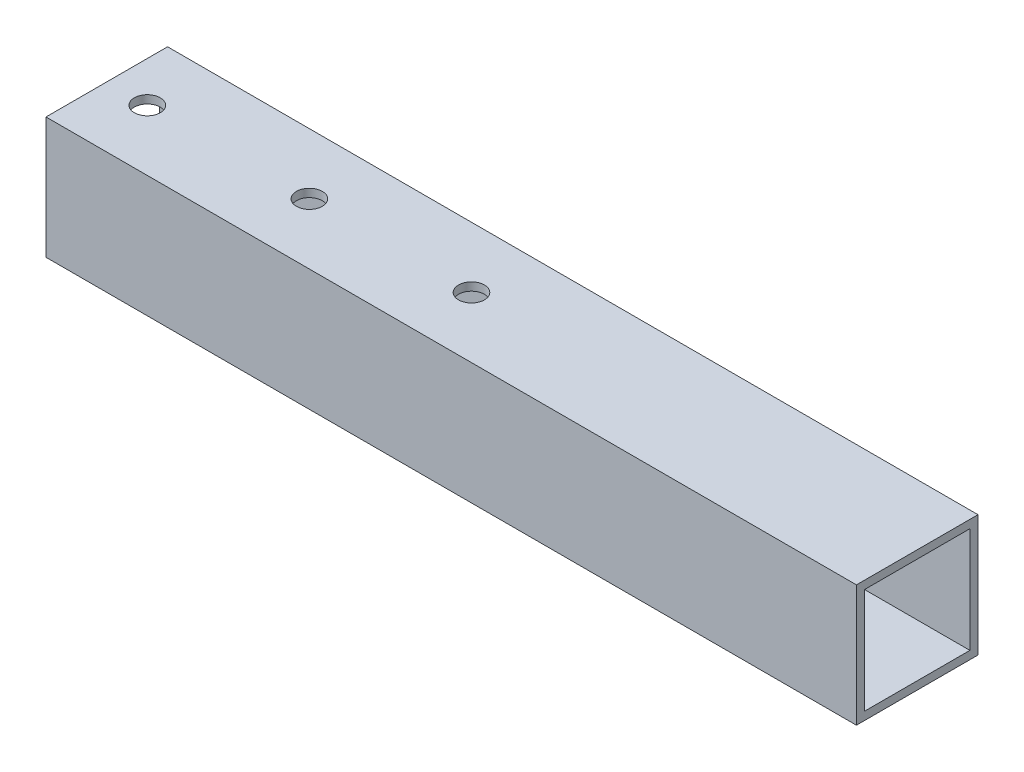
SolidWorks part; units mm, degrees
material "Thornel Mat VMA"
ref_plane "前视基准面" through (0, 0, 0) normal (0, 0, 1) x (1, 0, 0)
ref_plane "上视基准面" through (0, 0, 0) normal (0, 1, 0) x (1, 0, 0)
ref_plane "右视基准面" through (0, 0, 0) normal (1, 0, 0) x (0, 0, -1)
other "Configuration Table"
sketch "草图1" plane through (0, 0, 0) normal (0, 1, 0) x (1, 0, 0)
  line L0 (0, 0) -> (100, 0)
  dimension "D1" = 100
other "铝管 15X15X1(1)"
ref_plane "基准面1" through (0, 0, 0) normal (1, 0, 0) x (0, 0, -1)
sketch "草图11" plane through (0, 0, 0) normal (1, 0, 0) x (0, 0, -1)
  line L1 (-7.5, -7.5) -> (7.5, -7.5)
  line L2 (-7.5, -7.5) -> (-7.5, 7.5)
  line L3 (-7.5, 7.5) -> (7.5, 7.5)
  line L4 (7.5, -7.5) -> (7.5, 7.5)
  line L5 (-7.5, -7.5) -> (7.5, 7.5) construction
  line L6 (-7.5, 7.5) -> (7.5, -7.5) construction
  line L7 (-6.5, -6.5) -> (6.5, -6.5)
  line L8 (-6.5, -6.5) -> (-6.5, 6.5)
  line L9 (-6.5, 6.5) -> (6.5, 6.5)
  line L10 (6.5, -6.5) -> (6.5, 6.5)
  line L11 (-6.5, -6.5) -> (6.5, 6.5) construction
  line L12 (-6.5, 6.5) -> (6.5, -6.5) construction
  point P0 (0, 0)
  point P6 (0, 0)
  point P11 (0, 0)
  dimension "D1" = 15
  dimension "D2" = 15
  dimension "D3" = 13
  dimension "D4" = 13
sketch "草图12" plane through (0, 7.5, 0) normal (0, 1, 0) x (1, 0, 0)
  line L0 (0, 0) -> (100, 0) construction
  line L1 (100, 7.5) -> (100, -7.5) construction
  circle A0 centre (45, 0) radius 1.6
  circle A1 centre (25, 0) radius 1.6
  circle A2 centre (5, 0) radius 1.6
  dimension "D1" = 3.2
  dimension "D2" = 3.2
  dimension "D3" = 3.2
  dimension "D4" = 20
  dimension "D5" = 20
  dimension "D6" = 55
extrude "切除-拉伸1" cut sketch "草图12" against normal through all
